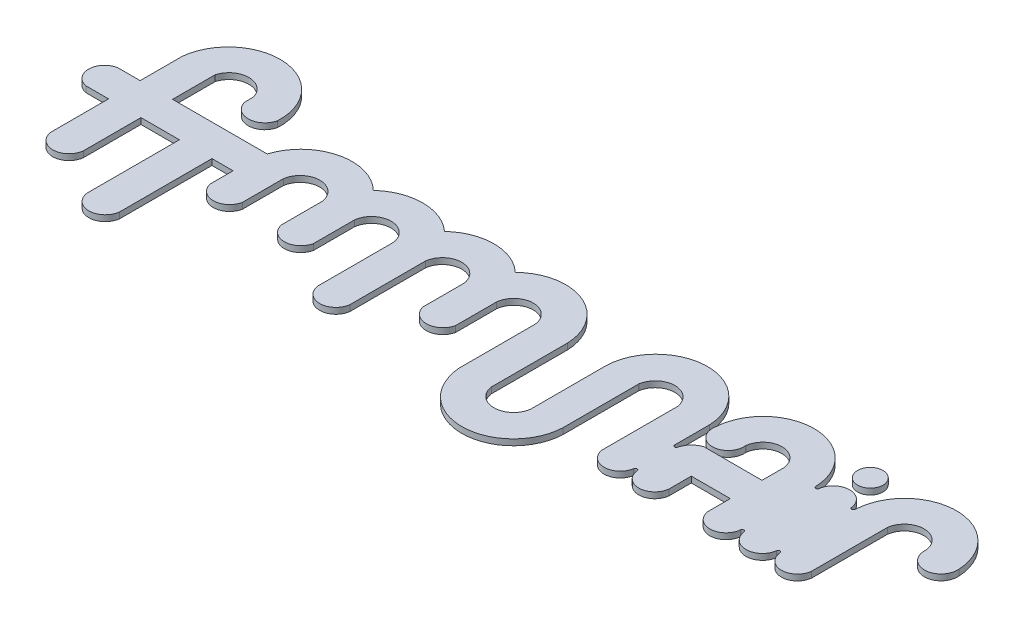
SolidWorks part; units mm, degrees
ref_plane "Front Plane" through (0, 0, 0) normal (0, 0, 1) x (1, 0, 0)
ref_plane "Top Plane" through (0, 0, 0) normal (0, 1, 0) x (1, 0, 0)
ref_plane "Right Plane" through (0, 0, 0) normal (1, 0, 0) x (0, 0, -1)
sketch "Sketch1" plane through (0, 0, 0) normal (0, 1, 0) x (1, 0, 0)
  line L0 (-116.9946, 16.9007) -> (-116.9946, 12.2502)
  line L1 (-113.9943, 12.2502) -> (-113.9943, 16.9007)
  line L2 (-113.9943, 16.9007) -> (-111.0895, 16.9007)
  line L3 (-111.0895, 16.9007) -> (-111.0895, 9.3568)
  line L4 (-108.0773, 9.3568) -> (-108.0773, 16.9007)
  line L5 (-108.0773, 16.9007) -> (-106.6196, 16.9007)
  line L6 (-106.6196, 16.9007) -> (-106.6196, 15.137)
  line L7 (-103.6514, 15.137) -> (-103.6514, 18.563)
  line L8 (-100.6995, 18.563) -> (-100.6995, 15.137)
  line L9 (-97.7168, 15.137) -> (-97.7168, 18.563)
  line L10 (-94.7738, 18.563) -> (-94.7738, 12.2502)
  line L11 (-91.7931, 12.2502) -> (-91.7931, 18.563)
  line L12 (-88.8847, 18.563) -> (-88.8847, 15.137)
  line L13 (-85.8797, 18.563) -> (-85.8797, 15.137)
  line L14 (-82.9638, 18.563) -> (-82.9638, 12.2502)
  line L15 (-79.9588, 18.563) -> (-79.9588, 12.2502)
  line L16 (-77.0206, 12.2502) -> (-77.0206, 18.563)
  line L17 (-74.0378, 18.563) -> (-74.0378, 12.2502)
  line L18 (-71.0978, 18.563) -> (-71.0978, 12.2502)
  line L19 (-68.1406, 15.6814) -> (-68.1406, 18.563)
  line L20 (-62.2481, 16.9007) -> (-62.2481, 18.563)
  line L21 (-53.3251, 18.563) -> (-53.3251, 12.2502)
  line L22 (-62.2481, 13.9582) -> (-62.2481, 12.2502)
  line L23 (-65.1983, 13.9582) -> (-65.1983, 12.2502)
  line L24 (-65.1983, 13.9582) -> (-62.2481, 13.9582)
  line L25 (-62.2481, 16.9007) -> (-66.9589, 16.9007)
  line L26 (-116.9946, 16.9007) -> (-118.7302, 16.9007)
  line L27 (-118.7302, 19.835) -> (-116.9946, 19.835)
  line L28 (-116.9946, 19.835) -> (-116.9946, 23.2141)
  line L29 (-113.9943, 19.835) -> (-113.9943, 23.2141)
  line L30 (-113.9943, 19.835) -> (-106.6196, 19.835)
  line L31 (-106.6196, 19.835) -> (-106.365, 19.835)
  line L32 (-111.0895, 23.1779) -> (-111.0895, 22.4986)
  arc A0 (-116.9946, 12.2502) -> (-113.9943, 12.2502) centre (-115.4945, 12.4086) ccw
  arc A1 (-111.0895, 9.3568) -> (-108.0773, 9.3568) centre (-109.5834, 9.5149) ccw
  arc A2 (-106.6196, 15.137) -> (-103.6514, 15.137) centre (-105.1355, 15.4301) ccw
  arc A3 (-103.6514, 18.563) -> (-100.6995, 18.563) centre (-102.1754, 18.3427) cw
  arc A4 (-100.6995, 15.137) -> (-97.7168, 15.137) centre (-99.2081, 15.4351) ccw
  arc A5 (-74.0378, 18.563) -> (-71.0978, 18.563) centre (-72.5678, 18.3245) cw
  arc A6 (-68.1406, 18.563) -> (-77.0206, 18.563) centre (-72.5806, 18.4003) ccw
  arc A7 (-59.2724, 18.563) -> (-56.2665, 18.563) centre (-57.7695, 18.354) cw
  arc A8 (-56.2665, 18.563) -> (-47.3348, 18.563) centre (-51.8006, 18.3366) cw
  arc A9 (-53.3251, 18.563) -> (-50.3836, 18.563) centre (-51.8543, 18.3665) cw
  arc A10 (-50.3836, 18.563) -> (-47.3348, 18.563) centre (-48.8592, 18.4267) ccw
  arc A11 (-62.2481, 12.2502) -> (-59.2724, 12.2502) centre (-60.7603, 12.4178) ccw
  arc A12 (-59.2724, 12.2502) -> (-56.2665, 12.2502) centre (-57.7695, 12.4564) ccw
  arc A13 (-56.2665, 12.2502) -> (-53.3251, 12.2502) centre (-54.7958, 12.3973) ccw
  arc A14 (-65.1312, 18.563) -> (-68.0545, 18.563) centre (-66.5929, 18.4231) cw
  arc A15 (-65.1983, 12.2502) -> (-68.1406, 12.2086) centre (-66.6717, 12.3897) cw
  arc A16 (-68.1406, 12.2086) -> (-71.0978, 12.2502) centre (-69.616, 12.4599) cw
  arc A17 (-77.0206, 12.2502) -> (-79.7559, 11.6503) centre (-78.4996, 12.4582) cw
  arc A19 (-82.7025, 11.004) -> (-74.0378, 12.2502) centre (-78.4846, 12.4231) ccw
  arc A21 (-88.8847, 15.137) -> (-85.8797, 15.137) centre (-87.3822, 15.4472) ccw
  arc A22 (-94.7738, 12.2502) -> (-91.7931, 12.2502) centre (-93.2834, 12.4323) ccw
  arc A23 (-97.7168, 18.563) -> (-94.7738, 18.563) centre (-96.2453, 18.3633) cw
  arc A24 (-91.7931, 18.563) -> (-88.8847, 18.563) centre (-90.3389, 18.3568) cw
  arc A25 (-85.8797, 18.563) -> (-82.9638, 18.563) centre (-84.4218, 18.396) cw
  arc A26 (-118.7302, 16.9007) -> (-118.7302, 19.835) centre (-118.4862, 18.3679) cw
  arc A27 (-106.365, 19.835) -> (-99.2081, 21.6807) centre (-102.1814, 18.4112) cw
  arc A28 (-99.2081, 21.6807) -> (-93.2834, 21.6807) centre (-96.2458, 18.2634) cw
  arc A29 (-93.2834, 21.6807) -> (-87.3822, 21.6807) centre (-90.3328, 18.3636) cw
  arc A30 (-87.3822, 21.6807) -> (-79.9588, 18.563) centre (-84.3886, 18.4119) cw
  arc A31 (-116.9946, 23.2141) -> (-108.0773, 22.4986) centre (-112.5461, 22.7301) cw
  arc A32 (-113.9943, 23.2141) -> (-111.0895, 23.1779) centre (-112.5471, 22.7848) cw
  arc A33 (-108.0773, 22.4986) -> (-111.0895, 22.4986) centre (-109.5834, 22.8167) cw
  arc A34 (-62.2481, 18.563) -> (-65.1312, 18.563) centre (-63.6897, 18.4073) ccw
  arc A35 (-68.0545, 18.563) -> (-59.2724, 18.563) centre (-63.6635, 18.4119) cw
  arc A36 (-68.1406, 15.6814) -> (-66.9589, 16.9007) centre (-66.4748, 15.2493) cw
  circle A37 centre (-57.7695, 21.4446) radius 1.2093
  arc A38 (-79.9588, 12.2502) -> (-79.7559, 11.6503) centre (-78.4228, 12.4354) ccw
  arc A39 (-82.9638, 12.2502) -> (-82.7025, 11.004) centre (-78.9875, 12.4335) ccw
extrude "Boss-Extrude1" add sketch "Sketch1" along normal blind 0.5
sketch "Sketch2" plane through (0, 0.5, 0) normal (0, 1, 0) x (1, 0, 0)
  line L0 (-65.3483, 12.2575) -> (-65.3483, 14.1082)
  line L1 (-68.2906, 15.6814) -> (-68.2906, 18.5602)
  line L2 (-76.8706, 18.5602) -> (-76.8706, 12.24)
  line L3 (-80.1088, 12.2414) -> (-80.1088, 18.5604)
  line L4 (-106.2562, 19.685) -> (-114.1443, 19.685)
  line L5 (-114.1443, 19.685) -> (-114.1443, 23.2353)
  line L6 (-110.9395, 23.1972) -> (-110.9395, 22.5147)
  line L7 (-116.8446, 23.2058) -> (-116.8446, 19.685)
  line L8 (-116.8446, 19.685) -> (-118.7175, 19.685)
  line L9 (-118.7175, 17.0507) -> (-116.8446, 17.0507)
  line L10 (-116.8446, 17.0507) -> (-116.8446, 12.2583)
  line L11 (-114.1443, 12.2583) -> (-114.1443, 17.0507)
  line L12 (-114.1443, 17.0507) -> (-110.9395, 17.0507)
  line L13 (-110.9395, 17.0507) -> (-110.9395, 9.3649)
  line L14 (-108.2273, 9.3649) -> (-108.2273, 17.0507)
  line L15 (-108.2273, 17.0507) -> (-106.4696, 17.0507)
  line L16 (-106.4696, 17.0507) -> (-106.4696, 15.152)
  line L17 (-103.8014, 15.152) -> (-103.8014, 18.5739)
  line L18 (-100.5495, 18.5739) -> (-100.5495, 15.1522)
  line L19 (-97.8668, 15.1522) -> (-97.8668, 18.5729)
  line L20 (-94.6238, 18.5729) -> (-94.6238, 12.2596)
  line L21 (-91.9431, 12.2596) -> (-91.9431, 18.5733)
  line L22 (-88.7347, 18.5733) -> (-88.7347, 15.1527)
  line L23 (-86.0297, 15.1527) -> (-86.0297, 18.5714)
  line L24 (-82.8138, 18.5714) -> (-82.8138, 12.2537)
  line L25 (-74.1878, 12.2532) -> (-74.1878, 18.563)
  line L26 (-70.9478, 18.563) -> (-70.9478, 12.2611)
  line L27 (-65.3483, 14.1082) -> (-62.0981, 14.1082)
  line L28 (-62.0981, 14.1082) -> (-62.0981, 12.2589)
  line L29 (-53.4751, 12.2502) -> (-53.4751, 18.5727)
  line L30 (-62.0981, 16.7507) -> (-66.9368, 16.7507)
  line L31 (-62.0981, 18.5709) -> (-62.0981, 16.7507)
  line L32 (-118.7302, 16.9007) -> (-116.9946, 16.9007)
  line L33 (-116.9946, 16.9007) -> (-116.9946, 12.2502)
  line L34 (-113.9943, 12.2502) -> (-113.9943, 16.9007)
  line L35 (-113.9943, 16.9007) -> (-111.0895, 16.9007)
  line L36 (-111.0895, 16.9007) -> (-111.0895, 9.3568)
  line L37 (-108.0773, 9.3568) -> (-108.0773, 16.9007)
  line L38 (-108.0773, 16.9007) -> (-106.6196, 16.9007)
  line L39 (-106.6196, 16.9007) -> (-106.6196, 15.137)
  line L40 (-103.6514, 15.137) -> (-103.6514, 18.563)
  line L41 (-100.6995, 18.563) -> (-100.6995, 15.137)
  line L42 (-97.7168, 15.137) -> (-97.7168, 18.563)
  line L43 (-94.7738, 18.563) -> (-94.7738, 12.2502)
  line L44 (-91.7931, 12.2502) -> (-91.7931, 18.563)
  line L45 (-88.8847, 18.563) -> (-88.8847, 15.137)
  line L46 (-85.8797, 15.137) -> (-85.8797, 18.563)
  line L47 (-82.9638, 18.563) -> (-82.9638, 12.2502)
  line L48 (-74.0378, 12.2502) -> (-74.0378, 18.563)
  line L49 (-71.0978, 18.563) -> (-71.0978, 12.2502)
  line L50 (-65.1983, 12.2502) -> (-65.1983, 13.9582)
  line L51 (-65.1983, 13.9582) -> (-62.2481, 13.9582)
  line L52 (-62.2481, 13.9582) -> (-62.2481, 12.2502)
  line L53 (-53.3251, 12.2502) -> (-53.3251, 18.563)
  line L54 (-62.2481, 18.563) -> (-62.2481, 16.9007)
  line L55 (-62.2481, 16.9007) -> (-66.9589, 16.9007)
  line L56 (-68.1406, 15.6814) -> (-68.1406, 18.563)
  line L57 (-77.0206, 18.563) -> (-77.0206, 12.2502)
  line L58 (-79.9588, 12.2502) -> (-79.9588, 18.563)
  line L59 (-106.365, 19.835) -> (-113.9943, 19.835)
  line L60 (-113.9943, 19.835) -> (-113.9943, 23.2141)
  line L61 (-111.0895, 23.1779) -> (-111.0895, 22.4986)
  line L62 (-116.9946, 23.2141) -> (-116.9946, 19.835)
  line L63 (-116.9946, 19.835) -> (-118.7302, 19.835)
  line L64 (-118.7302, 16.9007) -> (-116.9946, 16.9007)
  line L65 (-116.9946, 16.9007) -> (-116.9946, 12.2502)
  line L66 (-113.9943, 12.2502) -> (-113.9943, 16.9007)
  line L67 (-113.9943, 16.9007) -> (-111.0895, 16.9007)
  line L68 (-111.0895, 16.9007) -> (-111.0895, 9.3568)
  line L69 (-108.0773, 9.3568) -> (-108.0773, 16.9007)
  line L70 (-108.0773, 16.9007) -> (-106.6196, 16.9007)
  line L71 (-106.6196, 16.9007) -> (-106.6196, 15.137)
  line L72 (-103.6514, 15.137) -> (-103.6514, 18.563)
  line L73 (-100.6995, 18.563) -> (-100.6995, 15.137)
  line L74 (-97.7168, 15.137) -> (-97.7168, 18.563)
  line L75 (-94.7738, 18.563) -> (-94.7738, 12.2502)
  line L76 (-91.7931, 12.2502) -> (-91.7931, 18.563)
  line L77 (-88.8847, 18.563) -> (-88.8847, 15.137)
  line L78 (-85.8797, 15.137) -> (-85.8797, 18.563)
  line L79 (-82.9638, 18.563) -> (-82.9638, 12.2502)
  line L80 (-74.0378, 12.2502) -> (-74.0378, 18.563)
  line L81 (-71.0978, 18.563) -> (-71.0978, 12.2502)
  line L82 (-65.1983, 12.2502) -> (-65.1983, 13.9582)
  line L83 (-65.1983, 13.9582) -> (-62.2481, 13.9582)
  line L84 (-62.2481, 13.9582) -> (-62.2481, 12.2502)
  line L85 (-53.3251, 12.2502) -> (-53.3251, 18.563)
  line L86 (-62.2481, 18.563) -> (-62.2481, 16.9007)
  line L87 (-62.2481, 16.9007) -> (-66.9589, 16.9007)
  line L88 (-68.1406, 15.6814) -> (-68.1406, 18.563)
  line L89 (-77.0206, 18.563) -> (-77.0206, 12.2502)
  line L90 (-79.9588, 12.2502) -> (-79.9588, 18.563)
  line L91 (-106.365, 19.835) -> (-113.9943, 19.835)
  line L92 (-113.9943, 19.835) -> (-113.9943, 23.2141)
  line L93 (-111.0895, 23.1779) -> (-111.0895, 22.4986)
  line L94 (-116.9946, 23.2141) -> (-116.9946, 19.835)
  line L95 (-116.9946, 19.835) -> (-118.7302, 19.835)
  line L96 (-65.2803, 18.5791) -> (-65.2805, 18.5487)
  line L97 (-70.9478, 18.563) -> (-70.9478, 12.2502) construction
  line L98 (-65.3483, 12.2502) -> (-65.3483, 14.1082) construction
  line L99 (-62.0981, 16.7507) -> (-66.9589, 16.7507) construction
  line L100 (-47.4846, 18.5554) -> (-47.4842, 18.5496)
  line L101 (-67.9046, 18.5578) -> (-67.9052, 18.5487)
  line L102 (-68.2906, 15.6814) -> (-68.2906, 18.563) construction
  line L103 (-70.9497, 18.587) -> (-70.9478, 18.563)
  line L104 (-74.1859, 18.587) -> (-74.1878, 18.563)
  line L105 (-76.8706, 18.563) -> (-76.8706, 12.24) construction
  arc A0 (-79.8836, 11.5716) -> (-76.8706, 12.24) centre (-78.4996, 12.4582) ccw
  circle A1 centre (-57.7695, 21.4446) radius 1.2093
  circle A2 centre (-57.7695, 21.4446) radius 1.2093
  arc A3 (-80.1088, 12.2414) -> (-79.8836, 11.5716) centre (-78.4228, 12.4354) ccw
  arc A4 (-80.1088, 18.5604) -> (-87.3807, 21.4757) centre (-84.3886, 18.4119) ccw
  arc A5 (-87.3807, 21.4757) -> (-93.2821, 21.4783) centre (-90.3328, 18.3636) ccw
  arc A6 (-93.2821, 21.4783) -> (-99.2106, 21.4773) centre (-96.2458, 18.2634) ccw
  arc A7 (-99.2106, 21.4773) -> (-106.2562, 19.685) centre (-102.1814, 18.4112) ccw
  arc A8 (-110.9395, 23.1972) -> (-114.1443, 23.2353) centre (-112.5471, 22.7848) ccw
  arc A9 (-110.9395, 22.5147) -> (-108.2265, 22.5183) centre (-109.5834, 22.8167) ccw
  arc A10 (-108.2265, 22.5183) -> (-116.8446, 23.2058) centre (-112.5461, 22.7301) ccw
  arc A11 (-118.7175, 19.685) -> (-118.7175, 17.0507) centre (-118.4862, 18.3679) ccw
  arc A12 (-116.8446, 12.2583) -> (-114.1443, 12.2583) centre (-115.4945, 12.4086) ccw
  arc A13 (-110.9395, 9.3649) -> (-108.2273, 9.3649) centre (-109.5834, 9.5149) ccw
  arc A14 (-106.4696, 15.152) -> (-103.8014, 15.152) centre (-105.1355, 15.4301) ccw
  arc A15 (-100.5495, 18.5739) -> (-103.8014, 18.5739) centre (-102.1754, 18.3427) ccw
  arc A16 (-100.5495, 15.1522) -> (-97.8668, 15.1522) centre (-99.2081, 15.4351) ccw
  arc A17 (-94.6238, 18.5729) -> (-97.8668, 18.5729) centre (-96.2453, 18.3633) ccw
  arc A18 (-94.6238, 12.2596) -> (-91.9431, 12.2596) centre (-93.2834, 12.4323) ccw
  arc A19 (-88.7347, 18.5733) -> (-91.9431, 18.5733) centre (-90.3389, 18.3568) ccw
  arc A20 (-88.7347, 15.1527) -> (-86.0297, 15.1527) centre (-87.3822, 15.4472) ccw
  arc A21 (-82.8138, 18.5714) -> (-86.0297, 18.5714) centre (-84.4218, 18.396) ccw
  arc A22 (-82.8138, 12.2537) -> (-82.5613, 11.0549) centre (-78.9875, 12.4335) ccw
  arc A23 (-82.5613, 11.0549) -> (-74.1878, 12.2532) centre (-78.4846, 12.4231) ccw
  arc A24 (-70.9497, 18.587) -> (-74.1859, 18.587) centre (-72.5678, 18.3245) ccw
  arc A25 (-68.2906, 18.5602) -> (-76.8706, 18.5602) centre (-72.5806, 18.4003) ccw
  arc A26 (-70.9478, 12.2611) -> (-68.2885, 12.2338) centre (-69.616, 12.4599) ccw
  arc A27 (-67.9917, 12.227) -> (-65.3483, 12.2575) centre (-66.6717, 12.3897) ccw
  arc A28 (-68.2885, 12.2338) -> (-67.9917, 12.227) centre (-68.1401, 12.2304) cw
  arc A29 (-62.0981, 12.2589) -> (-59.4215, 12.267) centre (-60.7603, 12.4178) ccw
  arc A30 (-59.1238, 12.2706) -> (-56.4151, 12.2706) centre (-57.7695, 12.4564) ccw
  arc A31 (-56.1173, 12.2651) -> (-53.4743, 12.2651) centre (-54.7958, 12.3973) ccw
  arc A32 (-59.4215, 12.267) -> (-59.1238, 12.2706) centre (-59.2726, 12.2688) cw
  arc A33 (-56.4151, 12.2706) -> (-56.1173, 12.2651) centre (-56.2662, 12.2679) cw
  arc A34 (-50.2327, 18.5655) -> (-53.4751, 18.5727) centre (-51.8543, 18.3665) ccw
  arc A35 (-50.2327, 18.5655) -> (-47.4842, 18.5496) centre (-48.8592, 18.4267) ccw
  arc A36 (-47.4846, 18.5554) -> (-56.1167, 18.5554) centre (-51.8006, 18.3366) ccw
  arc A37 (-116.9946, 12.2502) -> (-113.9943, 12.2502) centre (-115.4945, 12.4086) ccw
  arc A38 (-111.0895, 9.3568) -> (-108.0773, 9.3568) centre (-109.5834, 9.5149) ccw
  arc A39 (-106.6196, 15.137) -> (-103.6514, 15.137) centre (-105.1355, 15.4301) ccw
  arc A40 (-100.6995, 18.563) -> (-103.6514, 18.563) centre (-102.1754, 18.3427) ccw
  arc A41 (-100.6995, 15.137) -> (-97.7168, 15.137) centre (-99.2081, 15.4351) ccw
  arc A42 (-94.7738, 18.563) -> (-97.7168, 18.563) centre (-96.2453, 18.3633) ccw
  arc A43 (-94.7738, 12.2502) -> (-91.7931, 12.2502) centre (-93.2834, 12.4323) ccw
  arc A44 (-88.8847, 18.563) -> (-91.7931, 18.563) centre (-90.3389, 18.3568) ccw
  arc A45 (-88.8847, 15.137) -> (-85.8797, 15.137) centre (-87.3822, 15.4472) ccw
  arc A46 (-82.9638, 18.563) -> (-85.8797, 18.563) centre (-84.4218, 18.396) ccw
  arc A47 (-82.9638, 12.2502) -> (-82.7025, 11.004) centre (-78.9875, 12.4335) ccw
  arc A48 (-82.7025, 11.004) -> (-74.0378, 12.2502) centre (-78.4846, 12.4231) ccw
  arc A49 (-71.0978, 18.563) -> (-74.0378, 18.563) centre (-72.5678, 18.3245) ccw
  arc A50 (-71.0978, 12.2502) -> (-68.1406, 12.2086) centre (-69.616, 12.4599) ccw
  arc A51 (-68.1406, 12.2086) -> (-65.1983, 12.2502) centre (-66.6717, 12.3897) ccw
  arc A52 (-62.2481, 12.2502) -> (-59.2724, 12.2502) centre (-60.7603, 12.4178) ccw
  arc A53 (-59.2724, 12.2502) -> (-56.2665, 12.2502) centre (-57.7695, 12.4564) ccw
  arc A54 (-56.2665, 12.2502) -> (-53.3251, 12.2502) centre (-54.7958, 12.3973) ccw
  arc A55 (-50.3836, 18.563) -> (-53.3251, 18.563) centre (-51.8543, 18.3665) ccw
  arc A56 (-50.3836, 18.563) -> (-47.3348, 18.563) centre (-48.8592, 18.4267) ccw
  arc A57 (-47.3348, 18.563) -> (-56.2665, 18.563) centre (-51.8006, 18.3366) ccw
  arc A58 (-56.2665, 18.563) -> (-59.2724, 18.563) centre (-57.7695, 18.354) ccw
  arc A59 (-59.2724, 18.563) -> (-68.0545, 18.563) centre (-63.6635, 18.4119) ccw
  arc A60 (-68.0545, 18.563) -> (-65.1312, 18.563) centre (-66.5929, 18.4231) ccw
  arc A61 (-62.2481, 18.563) -> (-65.1312, 18.563) centre (-63.6897, 18.4073) ccw
  arc A62 (-66.9589, 16.9007) -> (-68.1406, 15.6814) centre (-66.4748, 15.2493) ccw
  arc A63 (-68.1406, 18.563) -> (-77.0206, 18.563) centre (-72.5806, 18.4003) ccw
  arc A64 (-79.7559, 11.6503) -> (-77.0206, 12.2502) centre (-78.4996, 12.4582) ccw
  arc A65 (-79.9588, 12.2502) -> (-79.7559, 11.6503) centre (-78.4228, 12.4354) ccw
  arc A66 (-79.9588, 18.563) -> (-87.3822, 21.6807) centre (-84.3886, 18.4119) ccw
  arc A67 (-87.3822, 21.6807) -> (-93.2834, 21.6807) centre (-90.3328, 18.3636) ccw
  arc A68 (-93.2834, 21.6807) -> (-99.2081, 21.6807) centre (-96.2458, 18.2634) ccw
  arc A69 (-99.2081, 21.6807) -> (-106.365, 19.835) centre (-102.1814, 18.4112) ccw
  arc A70 (-111.0895, 23.1779) -> (-113.9943, 23.2141) centre (-112.5471, 22.7848) ccw
  arc A71 (-111.0895, 22.4986) -> (-108.0773, 22.4986) centre (-109.5834, 22.8167) ccw
  arc A72 (-108.0773, 22.4986) -> (-116.9946, 23.2141) centre (-112.5461, 22.7301) ccw
  arc A73 (-118.7302, 19.835) -> (-118.7302, 16.9007) centre (-118.4862, 18.3679) ccw
  arc A74 (-116.9946, 12.2502) -> (-113.9943, 12.2502) centre (-115.4945, 12.4086) ccw
  arc A75 (-111.0895, 9.3568) -> (-108.0773, 9.3568) centre (-109.5834, 9.5149) ccw
  arc A76 (-106.6196, 15.137) -> (-103.6514, 15.137) centre (-105.1355, 15.4301) ccw
  arc A77 (-100.6995, 18.563) -> (-103.6514, 18.563) centre (-102.1754, 18.3427) ccw
  arc A78 (-100.6995, 15.137) -> (-97.7168, 15.137) centre (-99.2081, 15.4351) ccw
  arc A79 (-94.7738, 18.563) -> (-97.7168, 18.563) centre (-96.2453, 18.3633) ccw
  arc A80 (-94.7738, 12.2502) -> (-91.7931, 12.2502) centre (-93.2834, 12.4323) ccw
  arc A81 (-88.8847, 18.563) -> (-91.7931, 18.563) centre (-90.3389, 18.3568) ccw
  arc A82 (-88.8847, 15.137) -> (-85.8797, 15.137) centre (-87.3822, 15.4472) ccw
  arc A83 (-82.9638, 18.563) -> (-85.8797, 18.563) centre (-84.4218, 18.396) ccw
  arc A84 (-82.9638, 12.2502) -> (-82.7025, 11.004) centre (-78.9875, 12.4335) ccw
  arc A85 (-82.7025, 11.004) -> (-74.0378, 12.2502) centre (-78.4846, 12.4231) ccw
  arc A86 (-71.0978, 18.563) -> (-74.0378, 18.563) centre (-72.5678, 18.3245) ccw
  arc A87 (-71.0978, 12.2502) -> (-68.1406, 12.2086) centre (-69.616, 12.4599) ccw
  arc A88 (-68.1406, 12.2086) -> (-65.1983, 12.2502) centre (-66.6717, 12.3897) ccw
  arc A89 (-62.2481, 12.2502) -> (-59.2724, 12.2502) centre (-60.7603, 12.4178) ccw
  arc A90 (-59.2724, 12.2502) -> (-56.2665, 12.2502) centre (-57.7695, 12.4564) ccw
  arc A91 (-56.2665, 12.2502) -> (-53.3251, 12.2502) centre (-54.7958, 12.3973) ccw
  arc A92 (-50.3836, 18.563) -> (-53.3251, 18.563) centre (-51.8543, 18.3665) ccw
  arc A93 (-50.3836, 18.563) -> (-47.3348, 18.563) centre (-48.8592, 18.4267) ccw
  arc A94 (-47.3348, 18.563) -> (-56.2665, 18.563) centre (-51.8006, 18.3366) ccw
  arc A95 (-56.2665, 18.563) -> (-59.2724, 18.563) centre (-57.7695, 18.354) ccw
  arc A96 (-59.2724, 18.563) -> (-68.0545, 18.563) centre (-63.6635, 18.4119) ccw
  arc A97 (-68.0545, 18.563) -> (-65.1312, 18.563) centre (-66.5929, 18.4231) ccw
  arc A98 (-62.2481, 18.563) -> (-65.1312, 18.563) centre (-63.6897, 18.4073) ccw
  arc A99 (-66.9589, 16.9007) -> (-68.1406, 15.6814) centre (-66.4748, 15.2493) ccw
  arc A100 (-68.1406, 18.563) -> (-77.0206, 18.563) centre (-72.5806, 18.4003) ccw
  arc A101 (-79.7559, 11.6503) -> (-77.0206, 12.2502) centre (-78.4996, 12.4582) ccw
  arc A102 (-79.9588, 12.2502) -> (-79.7559, 11.6503) centre (-78.4228, 12.4354) ccw
  arc A103 (-79.9588, 18.563) -> (-87.3822, 21.6807) centre (-84.3886, 18.4119) ccw
  arc A104 (-87.3822, 21.6807) -> (-93.2834, 21.6807) centre (-90.3328, 18.3636) ccw
  arc A105 (-93.2834, 21.6807) -> (-99.2081, 21.6807) centre (-96.2458, 18.2634) ccw
  arc A106 (-99.2081, 21.6807) -> (-106.365, 19.835) centre (-102.1814, 18.4112) ccw
  arc A107 (-111.0895, 23.1779) -> (-113.9943, 23.2141) centre (-112.5471, 22.7848) ccw
  arc A108 (-111.0895, 22.4986) -> (-108.0773, 22.4986) centre (-109.5834, 22.8167) ccw
  arc A109 (-108.0773, 22.4986) -> (-116.9946, 23.2141) centre (-112.5461, 22.7301) ccw
  arc A110 (-118.7302, 19.835) -> (-118.7302, 16.9007) centre (-118.4862, 18.3679) ccw
  arc A111 (-56.4151, 18.5423) -> (-59.1238, 18.5423) centre (-57.7695, 18.354) ccw
  arc A112 (-56.4151, 18.5423) -> (-56.1167, 18.5554) centre (-56.2659, 18.5489) ccw
  circle A113 centre (-57.7695, 21.4446) radius 1.0593
  arc A114 (-59.4223, 18.5578) -> (-67.9046, 18.5578) centre (-63.6635, 18.4119) ccw
  arc A115 (-59.4223, 18.5578) -> (-59.1238, 18.5423) centre (-59.2731, 18.5501) ccw
  arc A116 (-67.9052, 18.5487) -> (-65.2805, 18.5487) centre (-66.5929, 18.4231) ccw
  arc A117 (-62.0981, 18.5709) -> (-65.2803, 18.5791) centre (-63.6897, 18.4073) ccw
  arc A118 (-66.9368, 16.7507) -> (-67.9954, 15.6438) centre (-66.4748, 15.2493) ccw
  arc A119 (-68.2906, 15.6814) -> (-67.9954, 15.6438) centre (-68.143, 15.6626) ccw
  arc A120 (-70.9493, 12.2712) -> (-68.2885, 12.2338) centre (-69.616, 12.4599) ccw construction
  arc A121 (-67.9917, 12.227) -> (-65.3476, 12.2644) centre (-66.6717, 12.3897) ccw construction
  arc A122 (-66.9167, 16.7568) -> (-67.9954, 15.6438) centre (-66.4748, 15.2493) ccw construction
  arc A123 (-68.2905, 18.5575) -> (-76.8707, 18.5575) centre (-72.5806, 18.4003) ccw construction
  dimension "D1" = 0
  dimension "D2" = 0
  dimension "D3" = 0.15
  dimension "D4" = 0.15
  dimension "D5" = 0.15
  dimension "D6" = 0.15
  dimension "D7" = 0.15
  dimension "D8" = 0.15
  dimension "D9" = 0.15
  dimension "D10" = 0.15
  dimension "D11" = 0.15
  dimension "D12" = 0.15
  dimension "D13" = 0.15
  dimension "D14" = 0.15
  dimension "D15" = 0.15
  dimension "D16" = 0.15
  dimension "D17" = 0.15
  dimension "D18" = 0.15
  dimension "D19" = 0.15
extrude "Cut-Extrude1" cut sketch "Sketch2" against normal blind 10 contours L95 A110 L64 L65 A74 L66 L67 L68 A75 L69 L70 L71 A76 L72 A77 L73 A78 L74 A79 L75 A80 L76 A81 L77 A82 L78 A83 L79 A84 A85 L80 A86 L81 A87 A88 L82 L83 L84 A89 A90 A91 L85 A92 A93 A94 A95 A96 A97 A98 L86 L87 | A2 A113
